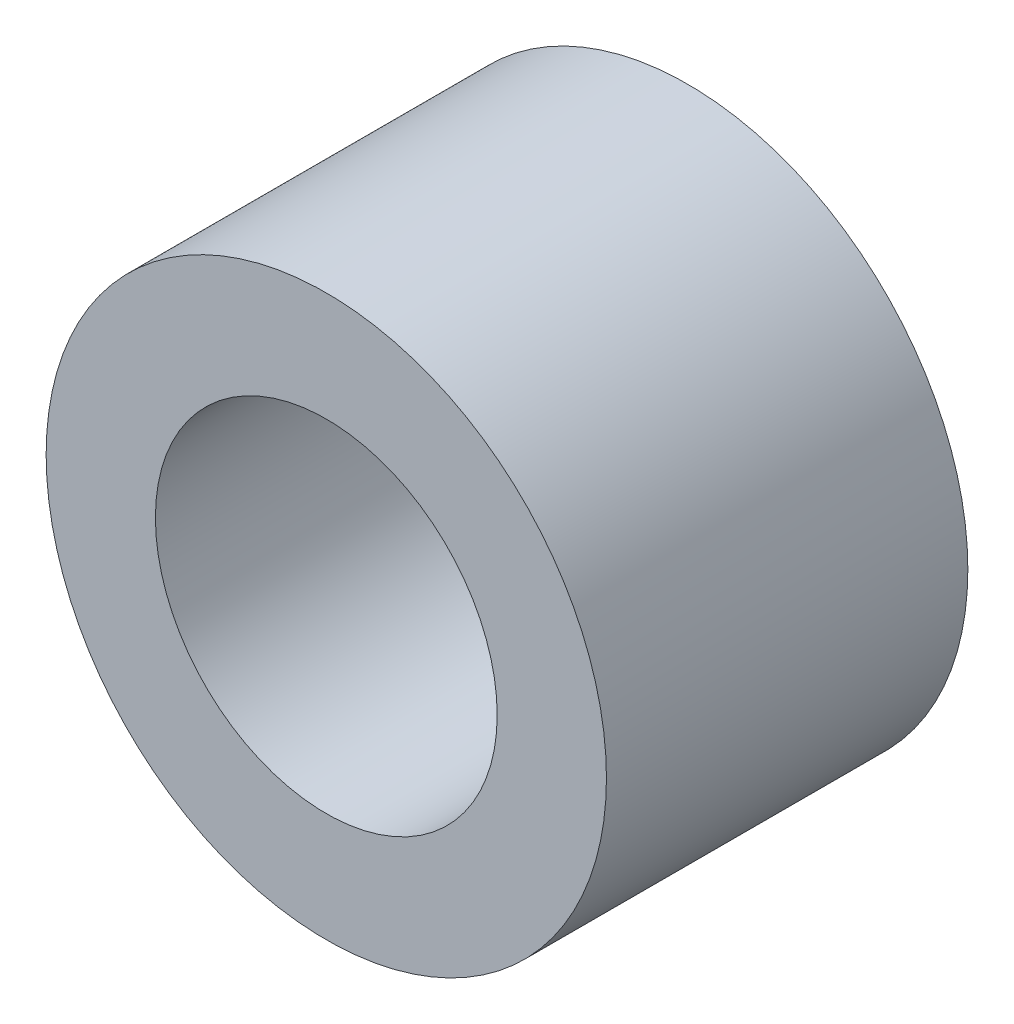
SolidWorks part; units mm, degrees
ref_plane "Plan de face" through (0, 0, 0) normal (0, 0, 1) x (1, 0, 0)
ref_plane "Plan de dessus" through (0, 0, 0) normal (0, 1, 0) x (1, 0, 0)
ref_plane "Plan de droite" through (0, 0, 0) normal (1, 0, 0) x (0, 0, -1)
sketch "Sketch1" plane through (0, 0, 0) normal (0, 0, 1) x (1, 0, 0)
  circle A0 centre (0, 0) radius 6.1
  circle A1 centre (0, 0) radius 10
  dimension "D1" = 12.2
  dimension "D2" = 20
extrude "Boss-Extrude1" add sketch "Sketch1" along normal mid plane 12.9
